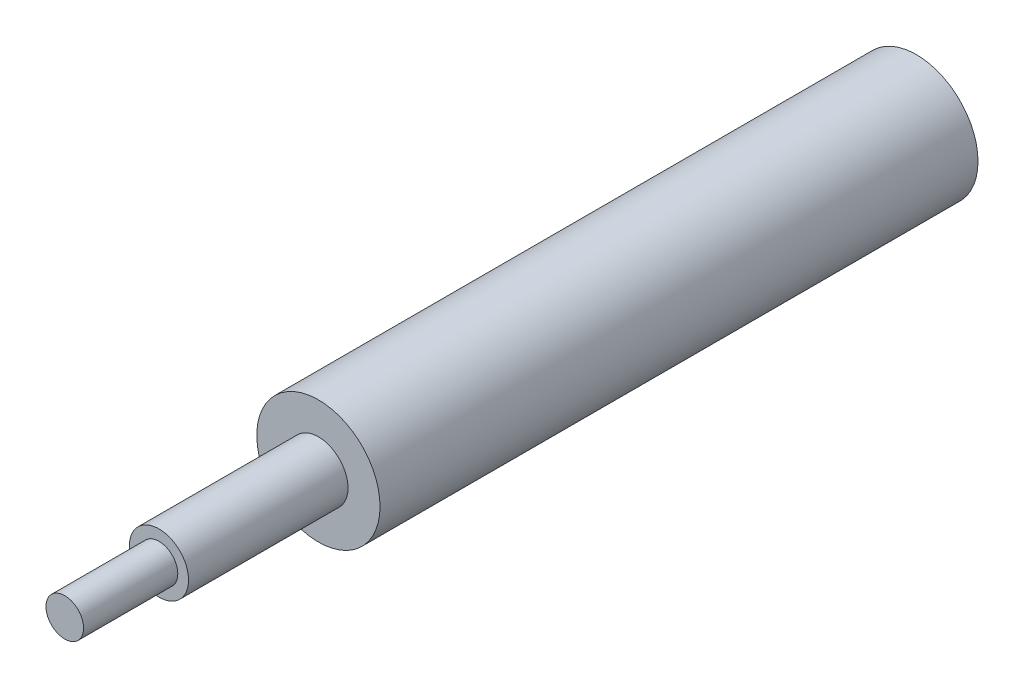
SolidWorks part; units mm, degrees
material "4032-T6"
ref_plane "Front Plane" through (0, 0, 0) normal (0, 0, 1) x (1, 0, 0)
ref_plane "Top Plane" through (0, 0, 0) normal (0, 1, 0) x (1, 0, 0)
ref_plane "Right Plane" through (0, 0, 0) normal (1, 0, 0) x (0, 0, -1)
sketch "Sketch1" plane through (0, 0, 0) normal (0, 0, 1) x (1, 0, 0)
  circle A0 centre (0, 0) radius 9.8171
  dimension "D1" = 19.6342
extrude "Boss-Extrude1" add sketch "Sketch1" along normal blind 95.25
sketch "Sketch3" plane through (0, 0, 95.25) normal (0, 0, 1) x (1, 0, 0)
  circle A0 centre (0, 0) radius 4.7125
  dimension "D1" = 9.425
extrude "Boss-Extrude3" add sketch "Sketch3" along normal blind 25.4
sketch "Sketch2" plane through (0, 0, 120.65) normal (0, 0, 1) x (1, 0, 0)
  circle A0 centre (0, 0) radius 3
extrude "Boss-Extrude2" add sketch "Sketch2" along normal blind 15
